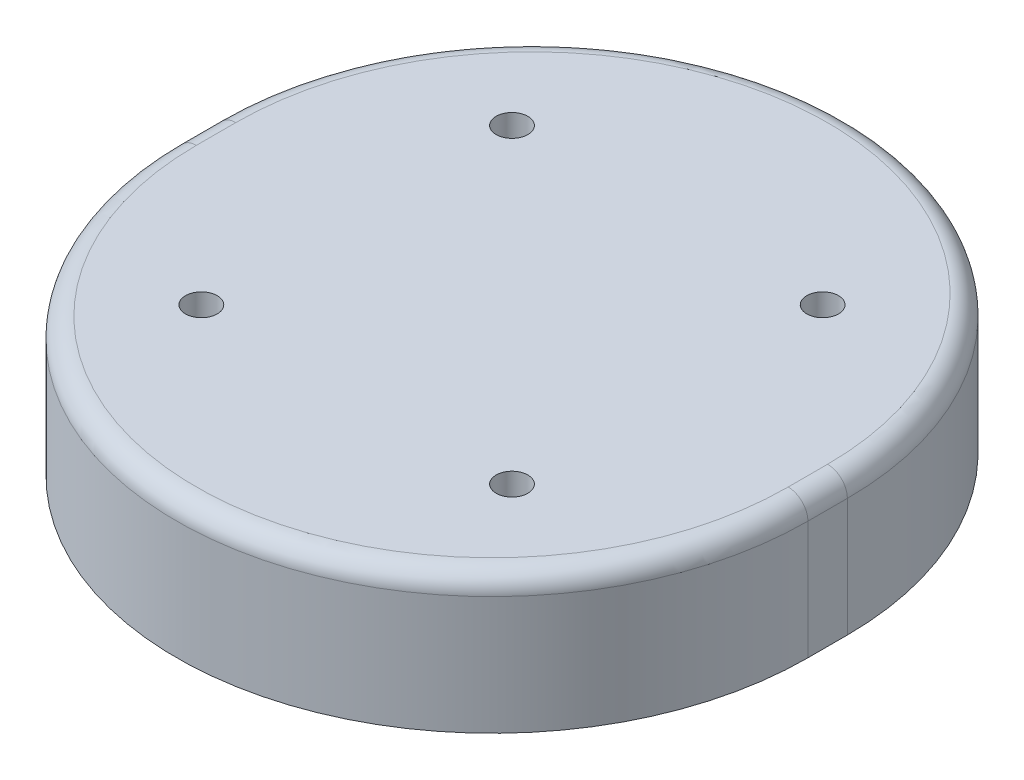
SolidWorks part; units mm, degrees
material "Fastray blue"
ref_plane "Front Plane" through (0, 0, 0) normal (0, 0, 1) x (1, 0, 0)
ref_plane "Top Plane" through (0, 0, 0) normal (0, 1, 0) x (1, 0, 0)
ref_plane "Right Plane" through (0, 0, 0) normal (1, 0, 0) x (0, 0, -1)
sketch "Sketch1" plane through (0, 0, 0) normal (0, 1, 0) x (1, 0, 0)
  line L0 (0, 3.175) -> (0, -3.175) construction
  line L1 (50.8, 3.175) -> (50.8, -3.175)
  line L2 (-50.8, 3.175) -> (-50.8, -3.175)
  arc A0 (50.8, 3.175) -> (-50.8, 3.175) centre (0, 3.175) ccw
  arc A1 (-50.8, -3.175) -> (50.8, -3.175) centre (0, -3.175) ccw
  point P3 (0, 0)
  point P15 (0, 0)
  dimension "D1" = 50.8
  dimension "D2" = 6.35
  dimension "D3" = 0
extrude "Boss-Extrude1" add sketch "Sketch1" along normal blind 22.225
sketch "Sketch4" plane through (0, 22.225, 0) normal (0, 1, 0) x (1, 0, 0)
  point P0 (-24.9999, 24.9999)
  point P5 (24.9999, 25)
  point P6 (25, -24.9999)
  point P7 (-24.9999, -24.9999)
  point P8 (0, 0)
  dimension "D1" = 24.9999
  dimension "D2" = 24.9999
hole_wizard "1/4-20 Tapped Hole1" positions "Sketch4" profile "Sketch5" tap size "1/4-20" standard "ANSI Inch"
sketch "Sketch5" plane through (-24.9999, 22.225, -24.9999) normal (1, 0, 0) x (0, 0, 1)
  line L0 (0, 0) -> (0, 14.2338)
  line L1 (0, 14.2338) -> (2.5527, 12.7)
  line L2 (2.5527, 12.7) -> (2.5527, 0)
  line L5 (2.5527, 0) -> (0, 0)
  line L10 (0, 14.2338) -> (-2.5527, 12.7) construction
  line L11 (0, -6.35) -> (0, 107.95) construction
  dimension "Tap Drill Dia." = 5.1054
  dimension "Tap Drill Depth" = 12.7
  dimension "Drill Angle" = 118
cosmetic thread "Hole Thread1" parameters "D1"=12.7, "D2"=6.35
cosmetic thread "Hole Thread2" parameters "D1"=12.7, "D2"=6.35
cosmetic thread "Hole Thread3" parameters "D1"=12.7, "D2"=6.35
cosmetic thread "Hole Thread4" parameters "D1"=12.7, "D2"=6.35
fillet "Fillet1" radius 3.175 4 edges at (50.8, 22.225, 0) (0, 22.225, 53.975) (-50.8, 22.225, 0) (0, 22.225, -53.975)
equation "\"D1@Sketch4\"=1.9685/2"
equation "\"D2@Sketch4\"=\"D1@Sketch4\""
